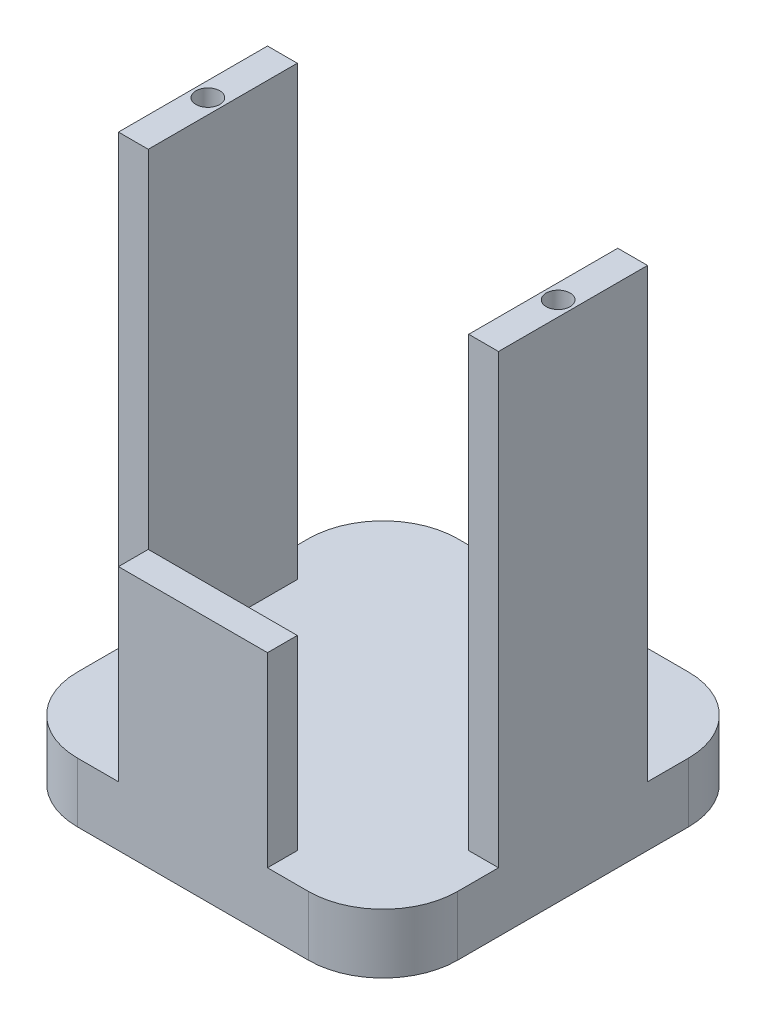
SolidWorks part; units mm, degrees
ref_plane "Plano frontal" through (0, 0, 0) normal (0, 0, 1) x (1, 0, 0)
ref_plane "Plano superior" through (0, 0, 0) normal (0, 1, 0) x (1, 0, 0)
ref_plane "Plano direito" through (0, 0, 0) normal (1, 0, 0) x (0, 0, -1)
sketch "Esboço1" plane through (0, 0, 0) normal (0, 1, 0) x (1, 0, 0)
  line L1 (-25.5, -25.5) -> (25.5, -25.5)
  line L2 (-25.5, -25.5) -> (-25.5, 25.5)
  line L3 (-25.5, 25.5) -> (25.5, 25.5)
  line L4 (25.5, -25.5) -> (25.5, 25.5)
  line L5 (-25.5, -25.5) -> (25.5, 25.5) construction
  line L6 (-25.5, 25.5) -> (25.5, -25.5) construction
  point P0 (0, 0)
  dimension "D1" = 51
  dimension "D2" = 51
extrude "Ressalto-extrusão1" add sketch "Esboço1" along normal blind 8
sketch "Esboço2" plane through (0, 8, 0) normal (0, 1, 0) x (1, 0, 0)
  line L5 (-25.5, 25.5) -> (-25.5, -25.5) construction
  line L10 (25.5, 25.5) -> (-25.5, 25.5) construction
  line L11 (-25.5, 10) -> (-21.5, 10)
  line L12 (-25.5, 10) -> (-25.5, -10)
  line L13 (-25.5, -10) -> (-21.5, -10)
  line L14 (-21.5, 10) -> (-21.5, -10)
  line L15 (0, 0) -> (0, 25.5) construction
  line L16 (25.5, -10) -> (21.5, -10)
  line L17 (21.5, 10) -> (21.5, -10)
  line L18 (25.5, 10) -> (21.5, 10)
  line L19 (25.5, 10) -> (25.5, -10)
  dimension "D1" = 20
  dimension "D2" = 15.5
  dimension "D3" = 4
extrude "Ressalto-extrusão2" add sketch "Esboço2" along normal blind 60
sketch "Esboço3" plane through (0, 68, 0) normal (0, 1, 0) x (1, 0, 0)
  line L0 (-23.5, 10) -> (-23.5, -10) construction
  line L1 (-21.5, 10) -> (-25.5, 10) construction
  line L2 (-25.5, -10) -> (-21.5, -10) construction
  line L3 (0, 0) -> (0, 25.5) construction
  line L4 (25.5, 25.5) -> (-25.5, 25.5) construction
  circle A0 centre (-23.5, 0) radius 1.6
  circle A1 centre (23.5, 0) radius 1.6
  dimension "D1" = 3.2
extrude "Corte-extrusão1" cut sketch "Esboço3" against normal blind 7
sketch "Esboço4" plane through (0, 8, 0) normal (0, 1, 0) x (1, 0, 0)
  line L0 (25.5, 25.5) -> (-25.5, 25.5) construction
  line L1 (-10, 25.5) -> (10, 25.5)
  line L2 (-10, 25.5) -> (-10, 21.5)
  line L3 (-10, 21.5) -> (10, 21.5)
  line L4 (10, 25.5) -> (10, 21.5)
  line L5 (-25.5, 25.5) -> (-25.5, 10) construction
  line L9 (0, 0) -> (-25.5, 0) construction
  line L10 (-25.5, 10) -> (-25.5, -10) construction
  line L11 (-10, -21.5) -> (10, -21.5)
  line L12 (10, -25.5) -> (10, -21.5)
  line L13 (-10, -25.5) -> (10, -25.5)
  line L14 (-10, -25.5) -> (-10, -21.5)
  dimension "D1" = 15.5
  dimension "D2" = 20
  dimension "D3" = 4
extrude "Ressalto-extrusão3" add sketch "Esboço4" along normal blind 25
sketch "Esboço5" plane through (0, 0, 0) normal (0, -1, 0) x (1, 0, 0)
  line L0 (0, 25.5) -> (0, -25.5) construction
  line L1 (-25.5, 25.5) -> (25.5, 25.5) construction
  line L2 (25.5, -25.5) -> (-25.5, -25.5) construction
  line L3 (-25.5, 0) -> (25.5, 0) construction
  line L4 (-25.5, -25.5) -> (-25.5, 25.5) construction
  line L5 (25.5, 25.5) -> (25.5, -25.5) construction
  line L6 (-25.5, 25.5) -> (25.5, -25.5) construction
  circle A0 centre (-11, 11) radius 1.6
  circle A1 centre (11, 11) radius 1.6
  circle A2 centre (11, -11) radius 1.6
  circle A3 centre (-11, -11) radius 1.6
  dimension "D1" = 3.2
  dimension "D2" = 11
extrude "Corte-extrusão2" cut sketch "Esboço5" against normal blind 7
fillet "Filete2" radius 10 4 edges at (-25.5, 4, -25.5) (25.5, 4, -25.5) (-25.5, 4, 25.5) (25.5, 4, 25.5)
